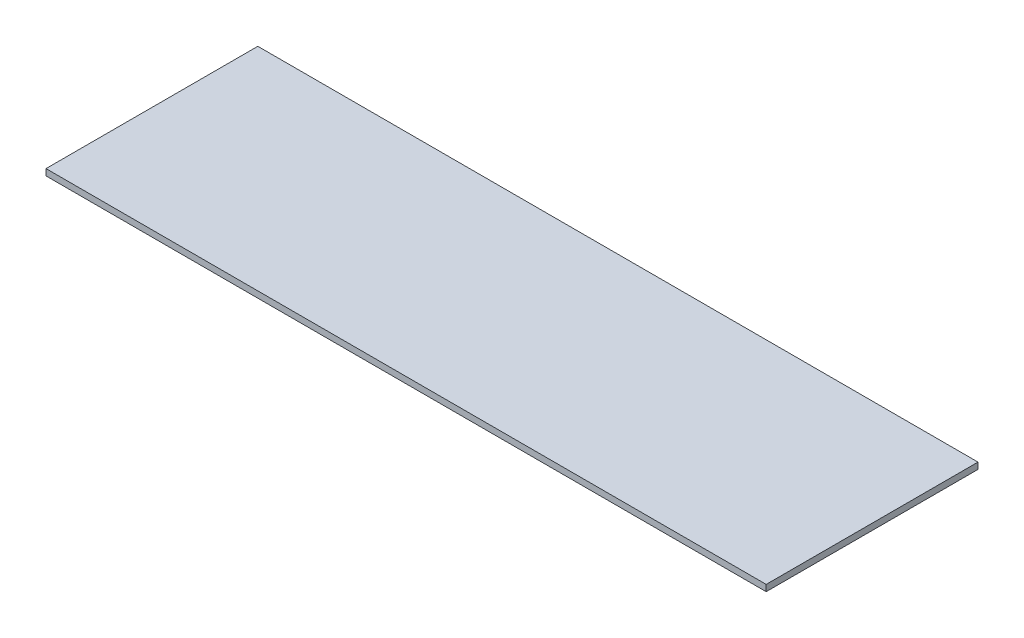
SolidWorks part; units mm, degrees
material "Pin"
ref_plane "Plan de face" through (0, 0, 0) normal (0, 0, 1) x (1, 0, 0)
ref_plane "Plan de dessus" through (0, 0, 0) normal (0, 1, 0) x (1, 0, 0)
ref_plane "Plan de droite" through (0, 0, 0) normal (1, 0, 0) x (0, 0, -1)
sketch "Esquisse1" plane through (0, 0, 0) normal (0, 1, 0) x (1, 0, 0)
  line L1 (0, 0) -> (2040, 0)
  line L2 (0, 0) -> (0, 600)
  line L3 (0, 600) -> (2040, 600)
  line L4 (2040, 0) -> (2040, 600)
  dimension "D1" = 600
  dimension "D2" = 2040
extrude "Boss.-Extru.1" add sketch "Esquisse1" along normal blind 18
